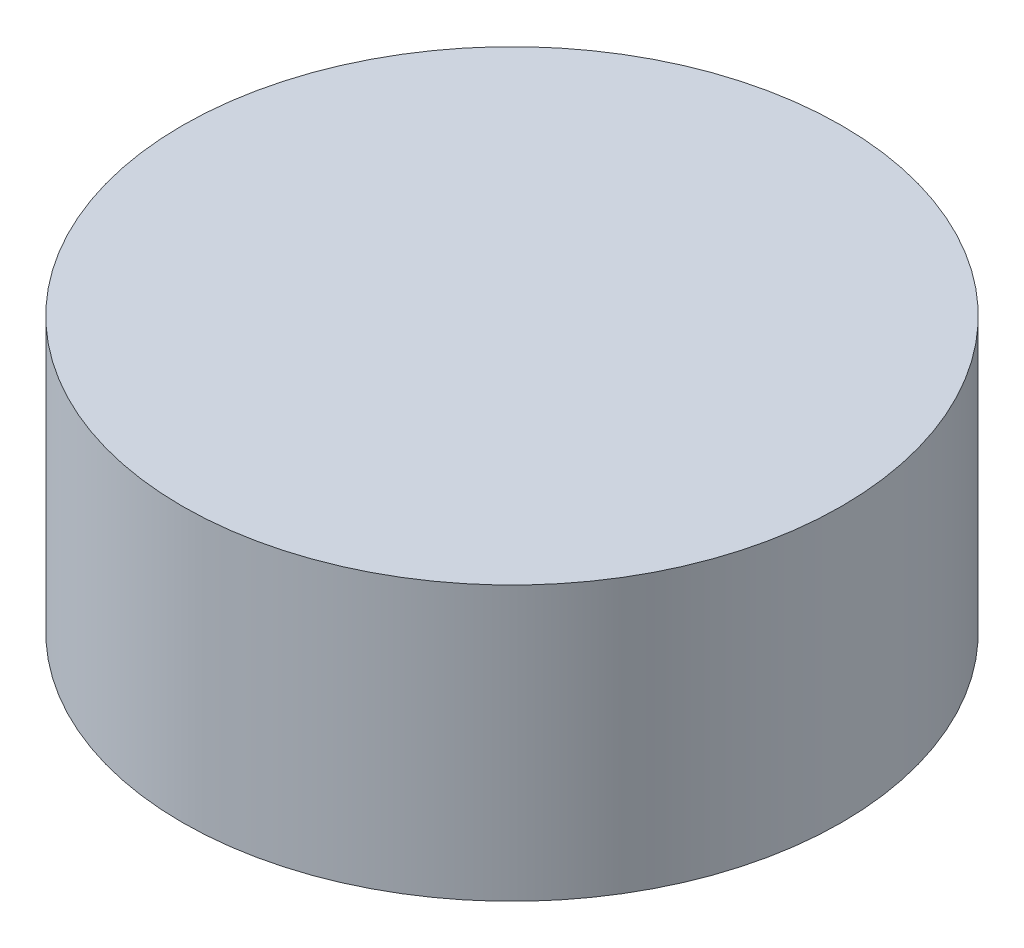
SolidWorks part; units mm, degrees
ref_plane "前视基准面" through (0, 0, 0) normal (0, 0, 1) x (1, 0, 0)
ref_plane "上视基准面" through (0, 0, 0) normal (0, 1, 0) x (1, 0, 0)
ref_plane "右视基准面" through (0, 0, 0) normal (1, 0, 0) x (0, 0, -1)
sketch "草图1" plane through (0, 0, 0) normal (0, 1, 0) x (1, 0, 0)
  circle A0 centre (0, 0) radius 32.5
extrude "凸台-拉伸1" add sketch "草图1" along normal blind 27
